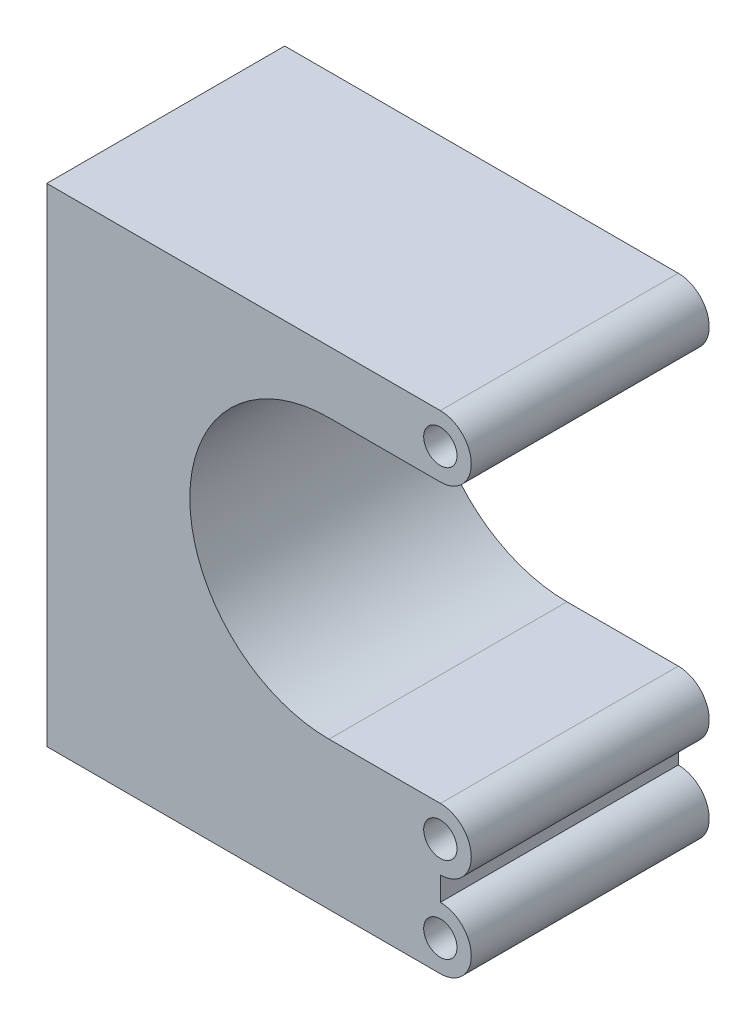
SolidWorks part; units mm, degrees
ref_plane "Front Plane" through (0, 0, 0) normal (0, 0, 1) x (1, 0, 0)
ref_plane "Top Plane" through (0, 0, 0) normal (0, 1, 0) x (1, 0, 0)
ref_plane "Right Plane" through (0, 0, 0) normal (1, 0, 0) x (0, 0, -1)
sketch "Sketch3" plane through (0, 0, 0) normal (0, 0, 1) x (1, 0, 0)
  line L0 (42.0127, -6.604) -> (30.1282, -6.604)
  line L1 (0, 0) -> (42.0127, 0)
  line L2 (0, 0) -> (0, -52.07)
  line L3 (0, -52.07) -> (42.0127, -52.07)
  line L4 (42.0127, 0) -> (42.0127, -6.604)
  line L5 (42.0127, -36.322) -> (30.1282, -36.322)
  line L6 (42.0127, -36.322) -> (42.0127, -52.07)
  arc A0 (30.1282, -6.604) -> (30.1282, -36.322) centre (30.1282, -21.463) ccw
  dimension "D1" = 15.748
  dimension "D4" = 42.0127
  dimension "D2" = 6.604
  dimension "D3" = 52.07
  dimension "D5" = 30.1282
extrude "Boss-Extrude1" add sketch "Sketch3" along normal blind 25.4
sketch "Sketch4" plane through (0, 0, 25.4) normal (0, 0, 1) x (1, 0, 0)
  line L0 (42.0127, -6.604) -> (42.0127, 0) construction
  line L1 (42.0127, -52.07) -> (42.0127, -36.322) construction
  line L2 (0, -52.07) -> (42.0127, -52.07) construction
  circle A0 centre (42.0127, -3.302) radius 3.302
  circle A1 centre (42.0127, -39.624) radius 3.302
  circle A2 centre (42.0127, -48.768) radius 3.302
  point P14 (0, 0)
  dimension "D1" = 6.604
  dimension "D2" = 6.604
extrude "Boss-Extrude2" add sketch "Sketch4" against normal blind 25.4
sketch "Sketch6" plane through (0, 0, 25.4) normal (0, 0, 1) x (1, 0, 0)
  line L0 (42.0127, 0) -> (42.0127, -6.604) construction
  line L1 (39.973, -3.302) -> (45.3147, -3.302) construction
  line L2 (42.0127, -45.466) -> (42.0127, -52.07) construction
  line L3 (50.1365, -48.768) -> (42.0127, -48.768) construction
  circle A0 centre (42.0127, -3.302) radius 1.778
  arc A1 (42.0127, -6.604) -> (42.0127, 0) centre (42.0127, -3.302) ccw construction
  circle A2 centre (42.0127, -39.624) radius 1.778
  arc A3 (42.0127, -52.07) -> (42.0127, -45.466) centre (42.0127, -48.768) ccw construction
  circle A4 centre (42.0127, -48.768) radius 1.778
  point P13 (42.0127, -3.302)
  dimension "D1" = 3.556
  dimension "D2" = 3.556
  dimension "D3" = 3.556
extrude "Cut-Extrude1" cut sketch "Sketch6" against normal through all
